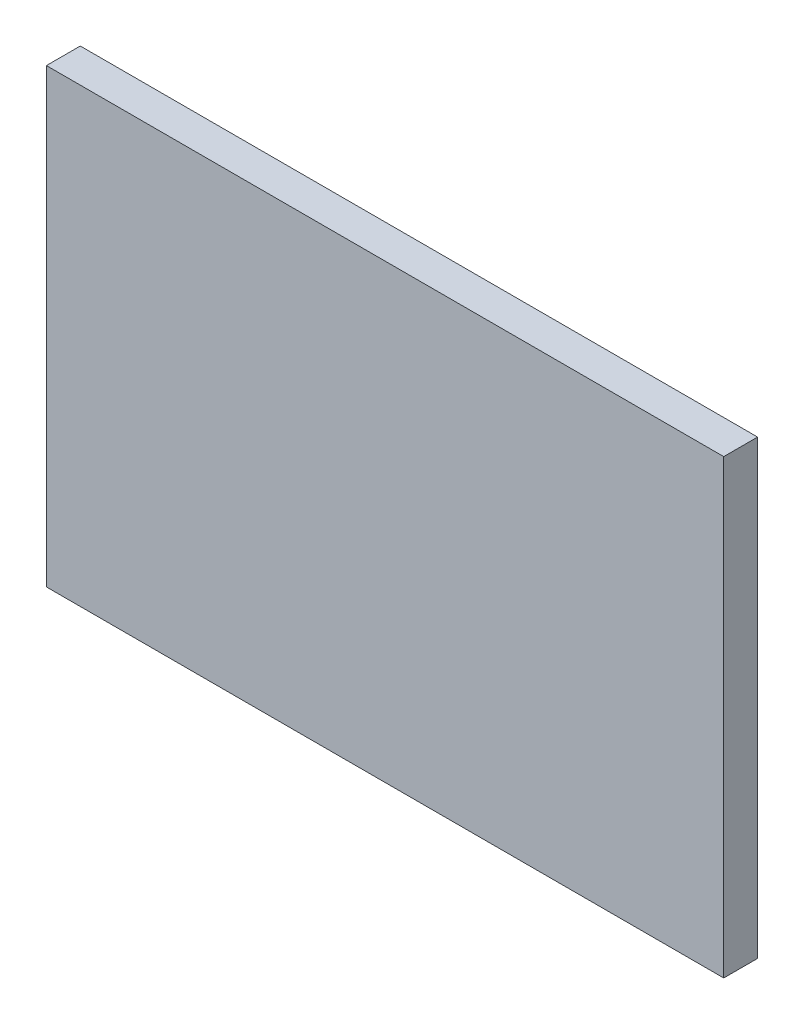
SolidWorks part; units mm, degrees
ref_plane "Plan de face" through (0, 0, 0) normal (0, 0, 1) x (1, 0, 0)
ref_plane "Plan de dessus" through (0, 0, 0) normal (0, 1, 0) x (1, 0, 0)
ref_plane "Plan de droite" through (0, 0, 0) normal (1, 0, 0) x (0, 0, -1)
sketch "Esquisse1" plane through (0, 0, 0) normal (0, 0, 1) x (1, 0, 0)
  line L1 (-112.8729, 69.0299) -> (37.1271, 69.0299)
  line L2 (-112.8729, 69.0299) -> (-112.8729, -30.9701)
  line L3 (-112.8729, -30.9701) -> (37.1271, -30.9701)
  line L4 (37.1271, 69.0299) -> (37.1271, -30.9701)
  dimension "D1" = 100
  dimension "D2" = 150
extrude "Boss.-Extru.1" add sketch "Esquisse1" along normal blind 7.5
